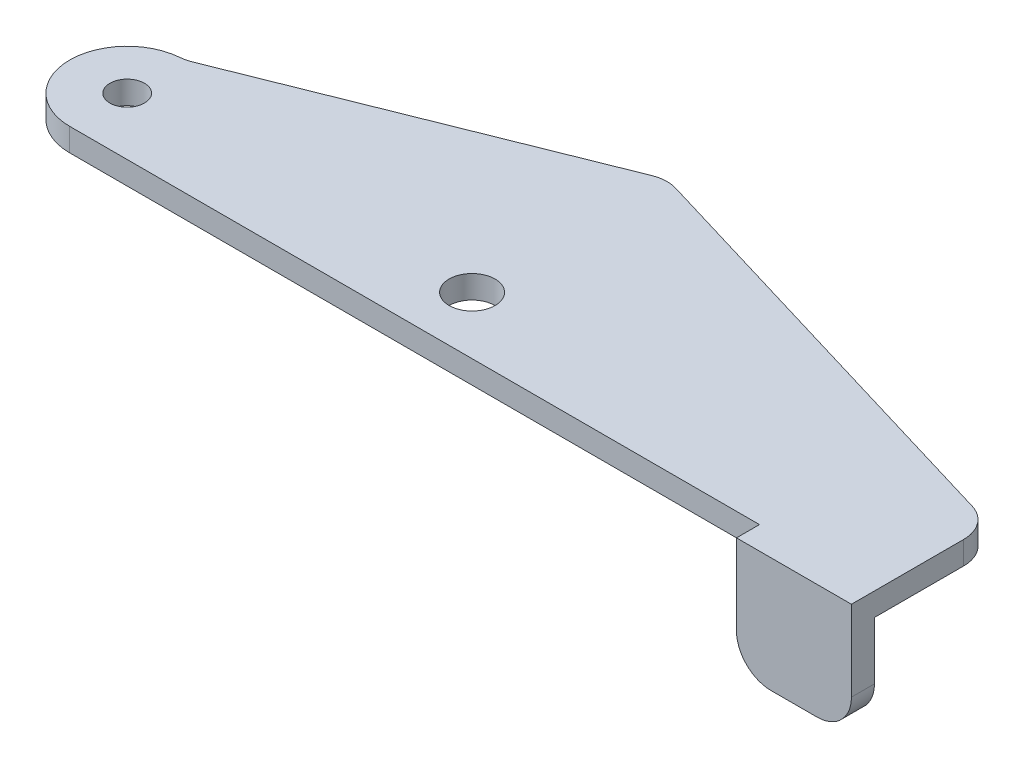
SolidWorks part; units mm, degrees
ref_plane "前视基准面" through (0, 0, 0) normal (0, 0, 1) x (1, 0, 0)
ref_plane "上视基准面" through (0, 0, 0) normal (0, 1, 0) x (1, 0, 0)
ref_plane "右视基准面" through (0, 0, 0) normal (1, 0, 0) x (0, 0, -1)
sketch "草图1" plane through (0, 0, 0) normal (0, 1, 0) x (1, 0, 0)
  line L0 (0, 55.5263) -> (0, -49.4908) construction
  line L1 (-51.7038, 0) -> (93.1474, 0) construction
  line L4 (-30, 5) -> (0, 17)
  line L5 (40, -5) -> (-30, -5)
  line L6 (0, 17) -> (40, 5)
  line L9 (40, 5) -> (40, -5)
  arc A0 (-30, 5) -> (-30, -5) centre (-30, 0) ccw
  circle A1 centre (-30, 0) radius 1.5
  circle A2 centre (0, 0) radius 2
  dimension "D3" = 3
  dimension "D7" = 4
  dimension "D4" = 17
  dimension "D1" = 10
  dimension "D2" = 30
  dimension "D5" = 5
  dimension "D6" = 40
  dimension "D8" = 10
extrude "凸台-拉伸1" add sketch "草图1" along normal blind 2
sketch "草图2" plane through (0, 2, 0) normal (0, 1, 0) x (1, 0, 0)
  line L0 (40, -5) -> (30, -5)
  line L1 (40, -5) -> (40, -7)
  line L2 (30, -5) -> (30, -7)
  line L3 (40, -7) -> (30, -7)
  line L5 (-30, -5) -> (40, -5) construction
  line L6 (40, -5) -> (40, 5) construction
  dimension "D1" = 2
  dimension "D2" = 10
extrude "凸台-拉伸2" add sketch "草图2" against normal blind 10
fillet "圆角1" radius 3 3 edges at (-30, 1, -5) (40, 1, -5) (0, 1, -17)
fillet "圆角2" radius 3 2 edges at (40, -8, 6) (30, -8, 6)
